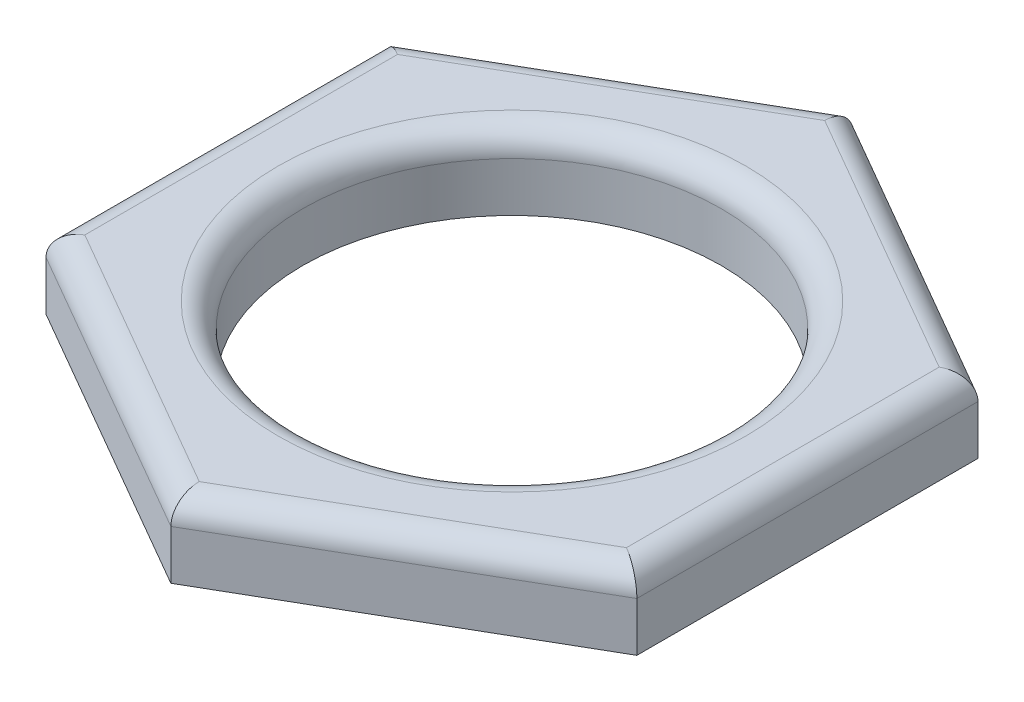
SolidWorks part; units mm, degrees
ref_plane "前视基准面" through (0, 0, 0) normal (0, 0, 1) x (1, 0, 0)
ref_plane "上视基准面" through (0, 0, 0) normal (0, 1, 0) x (1, 0, 0)
ref_plane "右视基准面" through (0, 0, 0) normal (1, 0, 0) x (0, 0, -1)
sketch "草图1" plane through (0, 0, 0) normal (0, 1, 0) x (1, 0, 0)
  line L0 (0, 25.0387) -> (0, -27.6045) construction
  line L1 (0, 13.8564) -> (-12, 6.9282)
  line L2 (-12, 6.9282) -> (-12, -6.9282)
  line L3 (-12, -6.9282) -> (0, -13.8564)
  line L4 (0, -13.8564) -> (12, -6.9282)
  line L5 (12, -6.9282) -> (12, 6.9282)
  line L6 (12, 6.9282) -> (0, 13.8564)
  circle A0 centre (0, 0) radius 8.5
  circle A1 centre (0, 0) radius 12 construction
  dimension "D1" = 17
  dimension "D2" = 24
extrude "凸台-拉伸1" add sketch "草图1" along normal blind 3
fillet "圆角1" radius 1 7 edges at (0, 3, 8.5) (12, 3, 0) (6, 3, 10.3923) (-6, 3, 10.3923) (-12, 3, 0) (-6, 3, -10.3923) (6, 3, -10.3923)
